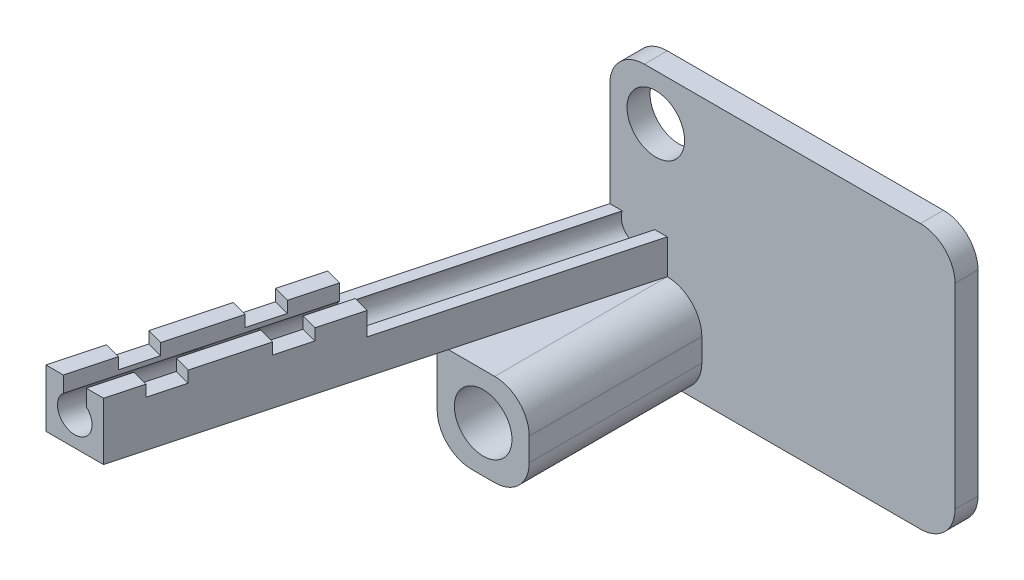
SolidWorks part; units mm, degrees
ref_plane "Alzado" through (0, 0, 0) normal (0, 0, 1) x (1, 0, 0)
ref_plane "Planta" through (0, 0, 0) normal (0, 1, 0) x (1, 0, 0)
ref_plane "Vista lateral" through (0, 0, 0) normal (1, 0, 0) x (0, 0, -1)
sketch "Croquis3" plane through (0, 0, 0) normal (0, 0, 1) x (1, 0, 0)
  line L0 (-63.169, 19.4366) -> (-33.169, 19.4366) construction
  line L1 (-63.169, 30.9366) -> (-33.169, 30.9366)
  line L2 (-63.169, 30.9366) -> (-63.169, 7.9366)
  line L3 (-63.169, 7.9366) -> (-33.169, 7.9366)
  line L4 (-33.169, 30.9366) -> (-33.169, 7.9366)
  circle A0 centre (-59.169, 26.9366) radius 2.5
  circle A1 centre (-59.169, 11.9366) radius 2.5
  dimension "D4" = 5
  dimension "D1" = 23
  dimension "D2" = 30
  dimension "D3" = 7.5
  dimension "D5" = 4
extrude "Saliente-Extruir2" add sketch "Croquis3" along normal blind 2
sketch "Croquis5" plane through (0, 0, 2) normal (0, 0, 1) x (1, 0, 0)
  line L1 (-63.169, 7.9366) -> (-55.169, 7.9366)
  line L2 (-63.169, 7.9366) -> (-63.169, 15.9366)
  line L3 (-63.169, 15.9366) -> (-55.169, 15.9366)
  line L4 (-55.169, 7.9366) -> (-55.169, 15.9366)
  circle A0 centre (-59.169, 11.9366) radius 2.5
  dimension "D1" = 8
  dimension "D2" = 8
extrude "Saliente-Extruir3" add sketch "Croquis5" along normal blind 15
sketch "Croquis6" plane through (0, 0, 2) normal (0, 0, 1) x (1, 0, 0)
  line L5 (-60.669, 19.9366) -> (-59.669, 19.9366) construction
  line L7 (-63.169, 15.9366) -> (-58.169, 15.9366)
  line L10 (-63.169, 15.9366) -> (-63.169, 20.9366)
  line L11 (-63.169, 20.9366) -> (-61.669, 20.9366)
  line L12 (-58.169, 15.9366) -> (-58.169, 20.9366)
  line L13 (-59.669, 19.5547) -> (-59.669, 20.9366)
  line L14 (-60.669, 19.9366) -> (-60.669, 20.9366) construction
  line L15 (-61.669, 19.5547) -> (-61.669, 20.9366)
  line L16 (-59.669, 20.9366) -> (-58.169, 20.9366)
  arc A3 (-61.669, 19.5547) -> (-59.669, 19.5547) centre (-60.669, 18.4366) ccw
  point P11 (-59.669, 20.2456)
  point P15 (-61.669, 20.2456)
  dimension "D3" = 3
  dimension "D1" = 5
  dimension "D2" = 5
sketch "Croquis7" plane through (0, 15.9366, 0) normal (0, 1, 0) x (1, 0, 0)
  line L0 (-63.169, -2) -> (-65.5426, -10.8582)
  line L1 (-63.169, -17) -> (-63.169, -2) construction
  dimension "D1" = 15
extrude "Saliente-Extruir4" add sketch "Croquis6" along direction (-0.2588, 0, 0.9659) on the side of the normal blind 40
fillet "Redondeo1" radius 3 6 edges at (-33.169, 7.9366, 1) (-33.169, 30.9366, 1) (-63.169, 7.9366, 8.5) (-63.169, 30.9366, 1) (-55.169, 7.9366, 9.5) (-55.169, 15.9366, 9.5)
sketch "Croquis10" plane through (0, 20.9366, 0) normal (0, 1, 0) x (1, 0, 0)
  line L0 (-58.169, -2) -> (-63.169, -2)
  line L1 (-63.169, -2) -> (-68.3454, -21.3185)
  line L2 (-73.5218, -40.637) -> (-63.169, -2) construction
  line L3 (-68.3454, -21.3185) -> (-63.6803, -22.5685)
  line L4 (-68.5218, -40.637) -> (-58.169, -2) construction
  line L5 (-63.6803, -22.5685) -> (-58.169, -2)
  dimension "D1" = 20
extrude "Cortar-Extruir2" cut sketch "Croquis10" against normal blind 2
sketch "Croquis11" plane through (0, 20.9366, 0) normal (0, 1, 0) x (1, 0, 0)
  line L0 (-64.6395, -26.1481) -> (-69.3046, -24.8981)
  line L1 (-68.5218, -40.637) -> (-63.6803, -22.5685) construction
  line L2 (-73.5218, -40.637) -> (-68.3454, -21.3185) construction
  line L3 (-69.3046, -24.8981) -> (-70.081, -27.7959)
  line L4 (-70.081, -27.7959) -> (-65.4159, -29.0459)
  line L5 (-65.4159, -29.0459) -> (-64.6395, -26.1481)
  line L6 (-66.9689, -34.8415) -> (-71.6339, -33.5915)
  line L7 (-71.6339, -33.5915) -> (-72.4104, -36.4893)
  line L8 (-72.4104, -36.4893) -> (-67.7453, -37.7393)
  line L9 (-67.7453, -37.7393) -> (-66.9689, -34.8415)
  dimension "D1" = 3
  dimension "D2" = 3
  dimension "D3" = 3
  dimension "D4" = 6
extrude "Cortar-Extruir3" cut sketch "Croquis11" against normal blind 1
